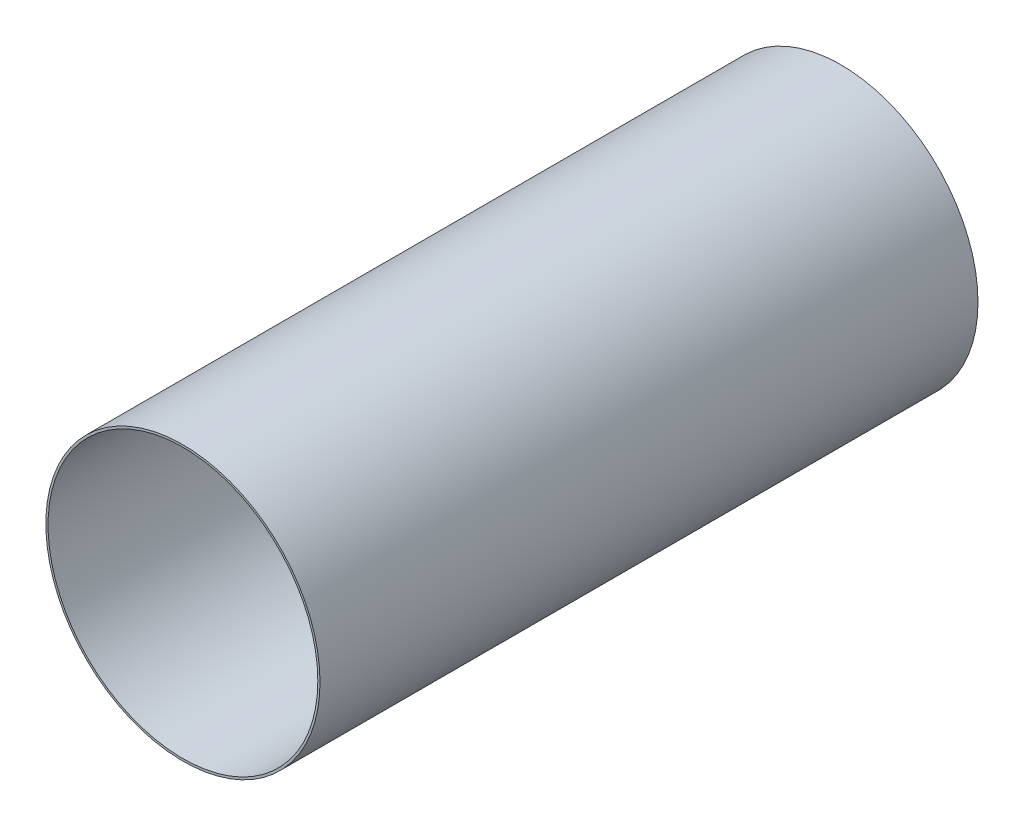
SolidWorks part; units mm, degrees
material "PVC Rigid"
ref_plane "Front Plane" through (0, 0, 0) normal (0, 0, 1) x (1, 0, 0)
ref_plane "Top Plane" through (0, 0, 0) normal (0, 1, 0) x (1, 0, 0)
ref_plane "Right Plane" through (0, 0, 0) normal (1, 0, 0) x (0, 0, -1)
sketch "Sketch1" plane through (0, 0, 0) normal (0, 0, 1) x (1, 0, 0)
  circle A0 centre (0, 0) radius 62.5
  circle A1 centre (0, 0) radius 61.5
  dimension "D1" = 125
  dimension "D2" = 123
extrude "Boss-Extrude1" add sketch "Sketch1" along normal mid plane 300
